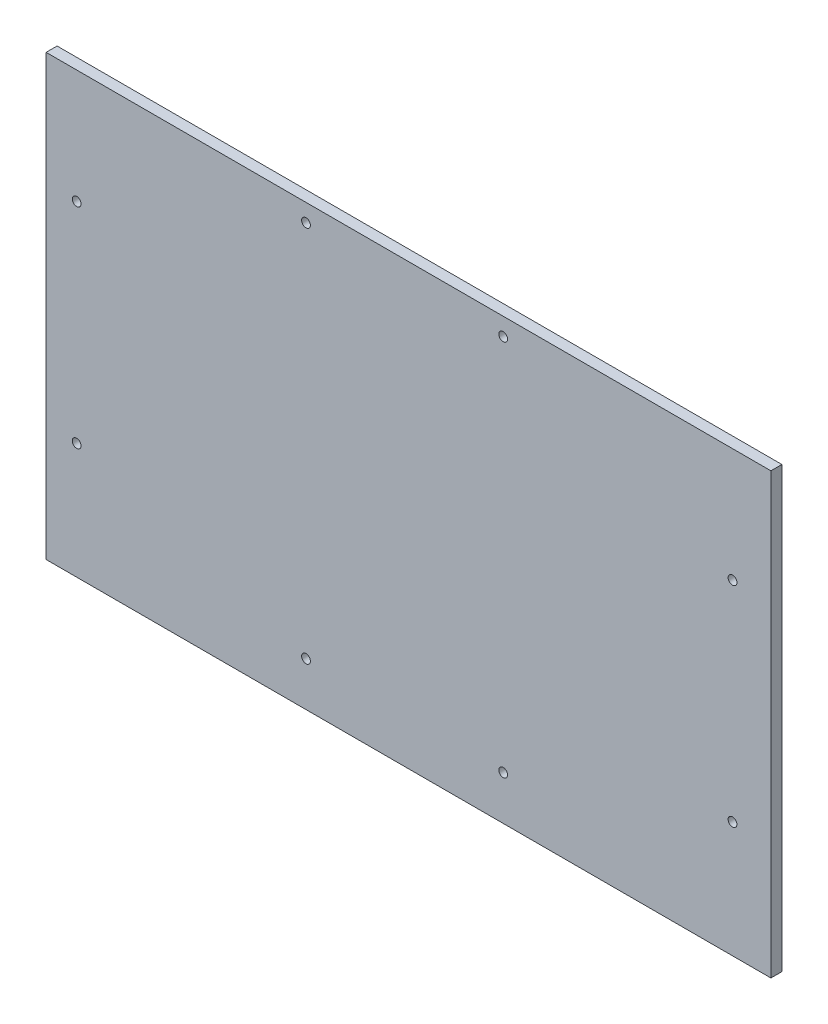
SolidWorks part; units mm, degrees
ref_plane "Front Plane" through (0, 0, 0) normal (0, 0, 1) x (1, 0, 0)
ref_plane "Top Plane" through (0, 0, 0) normal (0, 1, 0) x (1, 0, 0)
ref_plane "Right Plane" through (0, 0, 0) normal (1, 0, 0) x (0, 0, -1)
sketch "Sketch1" plane through (0, 0, 0) normal (0, 0, 1) x (1, 0, 0)
  line L6 (340.8986, -172.636) -> (10.8986, -172.636)
  line L7 (340.8986, -172.636) -> (340.8986, -372.636)
  line L8 (340.8986, -372.636) -> (10.8986, -372.636)
  line L9 (10.8986, -172.636) -> (10.8986, -372.636)
  dimension "D1" = 200
  dimension "D2" = 330
extrude "Boss-Extrude1" add sketch "Sketch1" along normal blind 5 contours L6 L9 L8 L7
sketch "Sketch2" plane through (0, 0, 5) normal (0, 0, 1) x (1, 0, 0)
  line L0 (174.111, -126.1867) -> (174.111, -420.1867) construction
  line L1 (94.2141, -126.1867) -> (254.0079, -126.1867) construction
  line L2 (254.0079, -420.1867) -> (94.2141, -420.1867) construction
  circle A0 centre (24.8019, -224.4713) radius 2
  circle A1 centre (24.8019, -319.8419) radius 2
  circle A2 centre (129.2314, -180.6865) radius 2
  circle A3 centre (129.2314, -352.5547) radius 2
  circle A4 centre (218.9906, -352.5547) radius 2
  circle A5 centre (323.4201, -319.8419) radius 2
  circle A6 centre (323.4201, -224.4713) radius 2
  circle A7 centre (218.9906, -180.6865) radius 2
extrude "Cut-Extrude1" cut sketch "Sketch2" against normal blind 10 and the other way blind 110
